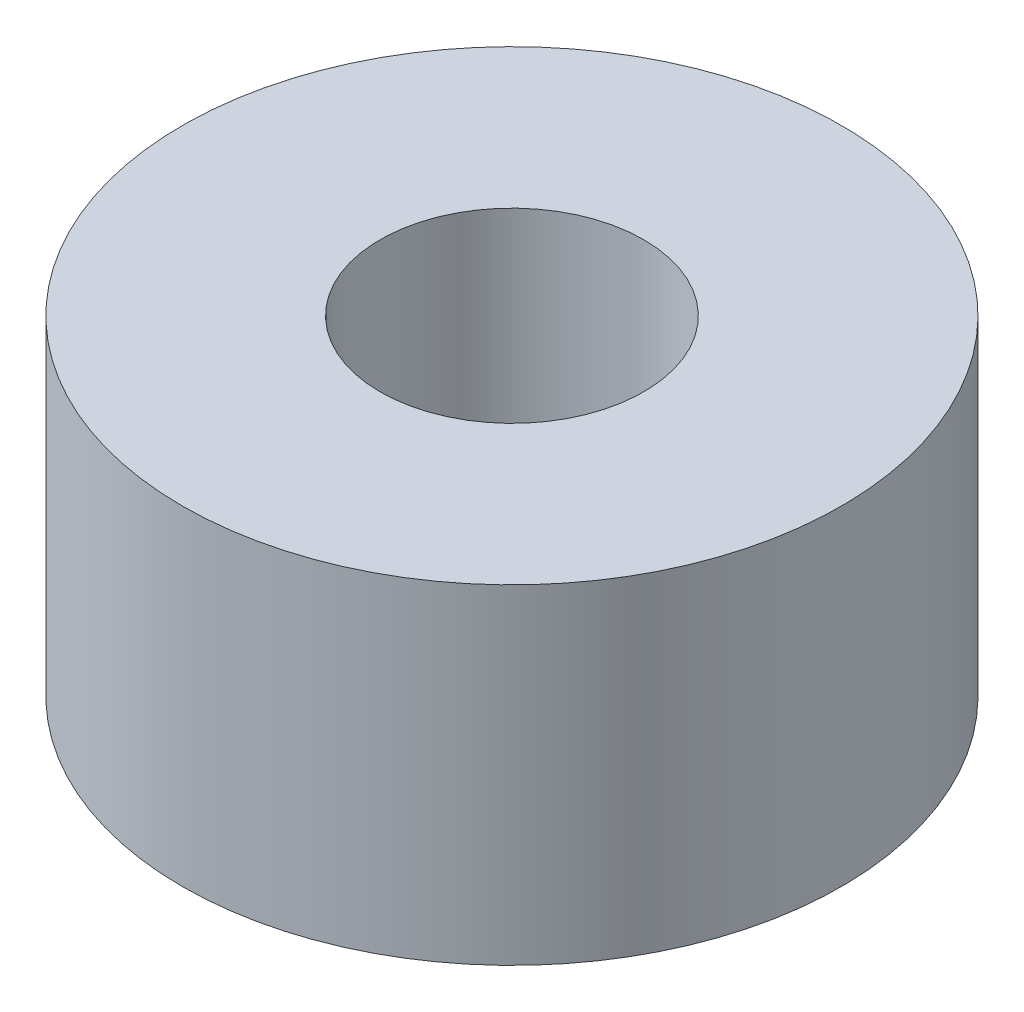
SolidWorks part; units mm, degrees
ref_plane "Plan de face" through (0, 0, 0) normal (0, 0, 1) x (1, 0, 0)
ref_plane "Plan de dessus" through (0, 0, 0) normal (0, 1, 0) x (1, 0, 0)
ref_plane "Plan de droite" through (0, 0, 0) normal (1, 0, 0) x (0, 0, -1)
sketch "Esquisse3" plane through (0, 0, 0) normal (0, 1, 0) x (1, 0, 0)
  circle A0 centre (0, 0) radius 4
  circle A1 centre (0, 0) radius 10
  dimension "D1" = 8
  dimension "D2" = 20
extrude "Boss.-Extru.2" add sketch "Esquisse3" along normal blind 10
